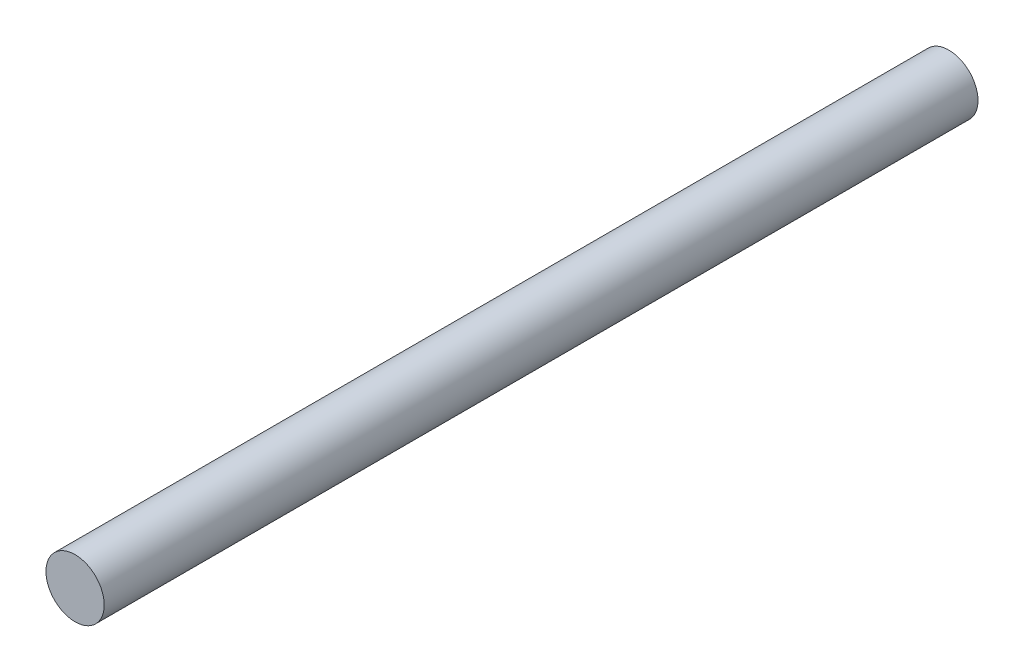
SolidWorks part; units mm, degrees
ref_plane "Спереди" through (0, 0, 0) normal (0, 0, 1) x (1, 0, 0)
ref_plane "Сверху" through (0, 0, 0) normal (0, 1, 0) x (1, 0, 0)
ref_plane "Справа" through (0, 0, 0) normal (1, 0, 0) x (0, 0, -1)
sketch "Эскиз1" plane through (0, 0, 0) normal (0, 0, 1) x (1, 0, 0)
  circle A0 centre (0, 0) radius 4
  dimension "D1" = 8
extrude "Бобышка-Вытянуть2" add sketch "Эскиз1" along normal blind 120
sketch "Эскиз2" plane through (0, 0, 0) normal (0, 0, -1) x (-1, 0, 0)
  line L0 (0, 4) -> (0, -4) construction
  line L1 (-3.9979, 0.1305) -> (3.9979, -0.1305) construction
  circle A0 centre (0, 0) radius 4 construction
sketch "Эскиз3" plane through (0, 0, 120) normal (0, 0, 1) x (1, 0, 0)
  line L0 (0, 0) -> (175.0376, -140.564) construction
ref_plane "Плоскость1" through (-3.9979, -0.1305, 0) normal (-0.9995, -0.0326, 0) x (0, 0, 1)
sketch "Эскиз4" plane through (-3.9979, -0.1305, 0) normal (-0.9995, -0.0326, 0) x (0, 0, 1)
  line L0 (59.788, 8.7234) -> (59.788, -8.6436) construction
equation "\"r\" = 8"
equation "\"D1@Эскиз1\"=\"r\""
equation "\"l\"=120"
equation "\"D1@Бобышка-Вытянуть2\"=\"l\""
